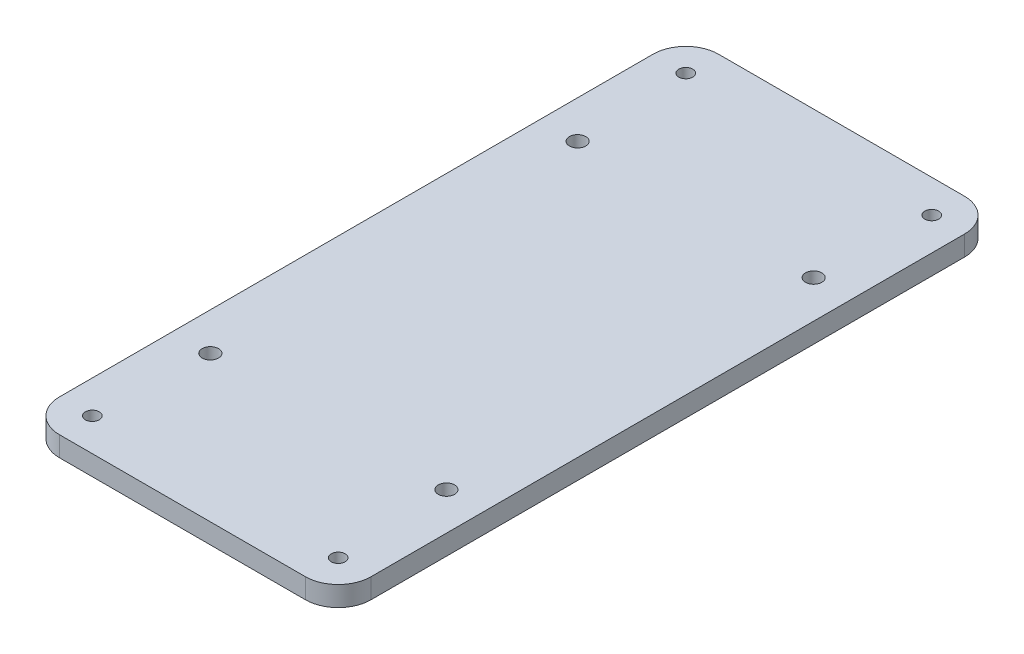
SolidWorks part; units mm, degrees
ref_plane "Front Plane" through (0, 0, 0) normal (0, 0, 1) x (1, 0, 0)
ref_plane "Top Plane" through (0, 0, 0) normal (0, 1, 0) x (1, 0, 0)
ref_plane "Right Plane" through (0, 0, 0) normal (1, 0, 0) x (0, 0, -1)
sketch "Sketch1" plane through (0, 0, 0) normal (0, 1, 0) x (1, 0, 0)
  line L0 (-37.5, 0) -> (37.5, 0) construction
  line L1 (-37.5, 90.5) -> (37.5, 90.5) construction
  line L2 (-37.5, 90.5) -> (-37.5, -90.5) construction
  line L3 (-37.5, -90.5) -> (37.5, -90.5) construction
  line L4 (37.5, 90.5) -> (37.5, -90.5) construction
  line L5 (0, 90.5) -> (0, -90.5) construction
  line L6 (-36, 0) -> (36, 0) construction
  line L7 (-36, -56) -> (36, -56) construction
  line L8 (-36, -56) -> (-36, 56) construction
  line L9 (-36, 56) -> (36, 56) construction
  line L10 (36, -56) -> (36, 56) construction
  line L11 (0, -56) -> (0, 56) construction
  line L12 (-37.5, 0) -> (-47.5, 0) construction
  line L13 (-37.5, 100.5) -> (37.5, 100.5)
  line L14 (-47.5, 90.5) -> (-47.5, -90.5)
  line L15 (-37.5, -100.5) -> (37.5, -100.5)
  line L16 (47.5, 90.5) -> (47.5, -90.5)
  line L17 (47.5, 0) -> (37.5, 0) construction
  line L18 (0, 90.5) -> (0, 100.5) construction
  line L19 (0, -90.5) -> (0, -100.5) construction
  arc A0 (-47.5, 90.5) -> (-37.5, 100.5) centre (-37.5, 90.5) cw
  arc A1 (-47.5, -90.5) -> (-37.5, -100.5) centre (-37.5, -90.5) ccw
  arc A2 (37.5, -100.5) -> (47.5, -90.5) centre (37.5, -90.5) ccw
  arc A3 (47.5, 90.5) -> (37.5, 100.5) centre (37.5, 90.5) ccw
  circle A4 centre (-36, 56) radius 2.5
  circle A5 centre (36, 56) radius 2.5
  circle A6 centre (36, -56) radius 2.5
  circle A7 centre (-36, -56) radius 2.5
  circle A8 centre (-37.5, 90.5) radius 2.125
  circle A9 centre (37.5, 90.5) radius 2.125
  circle A10 centre (37.5, -90.5) radius 2.125
  circle A11 centre (-37.5, -90.5) radius 2.125
  point P8 (0, 0)
  point P18 (0, 0)
  dimension "D6" = 10
  dimension "D7" = 5
  dimension "D8" = 4.25
  dimension "D1" = 75
  dimension "D2" = 181
  dimension "D3" = 72
  dimension "D4" = 112
  dimension "D5" = 10
extrude "Boss-Extrude1" add sketch "Sketch1" along normal blind 6.096
